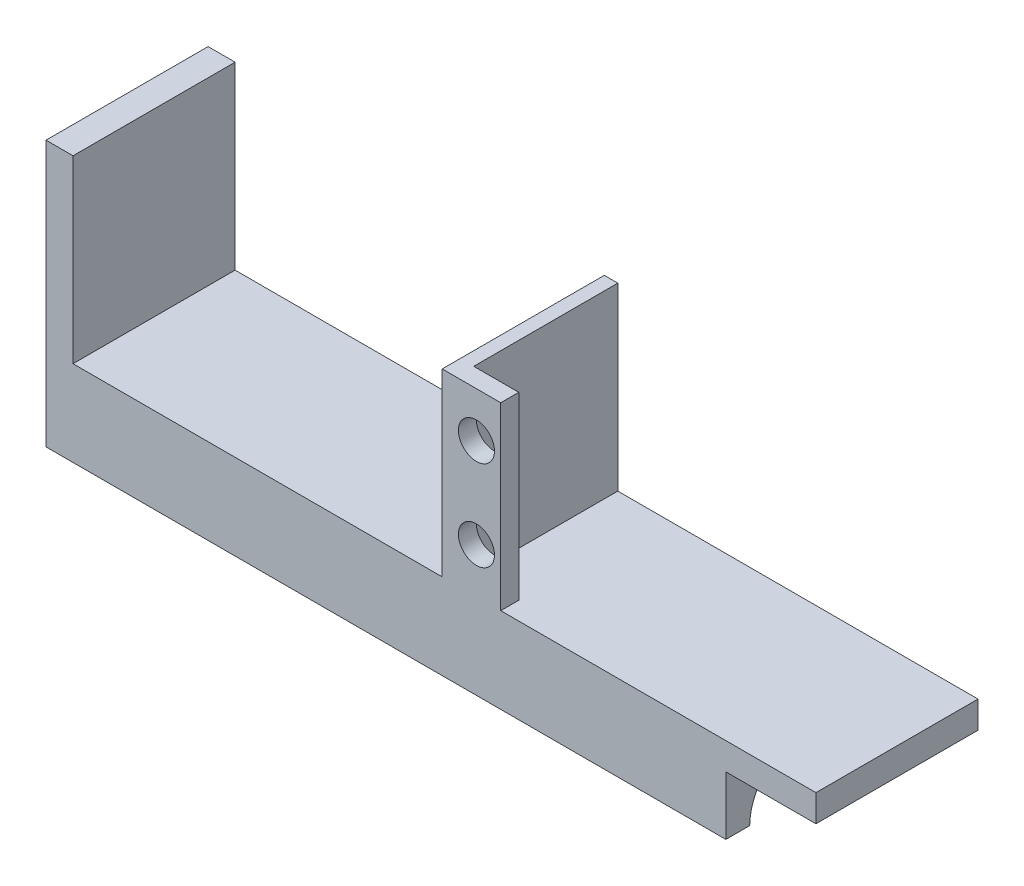
SolidWorks part; units mm, degrees
ref_plane "Front Plane" through (0, 0, 0) normal (0, 0, 1) x (1, 0, 0)
ref_plane "Top Plane" through (0, 0, 0) normal (0, 1, 0) x (1, 0, 0)
ref_plane "Right Plane" through (0, 0, 0) normal (1, 0, 0) x (0, 0, -1)
sketch "Sketch1" plane through (0, 0, 0) normal (0, 1, 0) x (1, 0, 0)
  line L1 (-22.75, -9) -> (22.75, -9)
  line L2 (-22.75, -9) -> (-22.75, 9)
  line L3 (-22.75, 9) -> (22.75, 9)
  line L4 (22.75, -9) -> (22.75, 9)
  line L5 (-22.75, -9) -> (22.75, 9) construction
  line L6 (-22.75, 9) -> (22.75, -9) construction
  point P0 (0, 0)
  dimension "D1" = 45.5
  dimension "D2" = 18
extrude "Boss-Extrude1" add sketch "Sketch1" along normal blind 3 contours L2 L3 L4 L1
sketch "Sketch2" plane through (0, 3, 0) normal (0, 1, 0) x (1, 0, 0)
  line L0 (-22.75, -9) -> (22.75, -9) construction
  line L1 (-22.75, 9) -> (-19.75, 9)
  line L2 (-22.75, 9) -> (-22.75, -9)
  line L3 (-22.75, -9) -> (-19.75, -9)
  line L4 (-19.75, 9) -> (-19.75, -9)
  line L16 (22.75, 9) -> (21.25, 9)
  line L17 (22.75, 9) -> (22.75, -9)
  line L18 (22.75, -9) -> (21.25, -9)
  line L19 (21.25, 9) -> (21.25, -9)
  dimension "D1" = 3
  dimension "D2" = 1.5
extrude "Boss-Extrude2" add sketch "Sketch2" along normal blind 20
sketch "Sketch6" plane through (22.75, 0, 0) normal (1, 0, 0) x (0, 0, -1)
  line L1 (-9, 23) -> (-7, 23)
  line L2 (-9, 23) -> (-9, 3)
  line L3 (-9, 3) -> (-7, 3)
  line L4 (-7, 23) -> (-7, 3)
  dimension "D1" = 20
  dimension "D2" = 2
extrude "Boss-Extrude5" add sketch "Sketch6" along normal blind 5
sketch "Sketch7" plane through (0, 0, 9) normal (0, 0, 1) x (1, 0, 0)
  line L0 (27.75, 23) -> (27.75, 3) construction
  line L1 (27.75, 3) -> (22.75, 3) construction
  line L2 (21.25, 23) -> (27.75, 23) construction
  circle A0 centre (25.05, 8) radius 2
  circle A1 centre (25.05, 18) radius 2
  dimension "D1" = 4
  dimension "D4" = 4
  dimension "D2" = 2.7
  dimension "D3" = 5
  dimension "D5" = 5
extrude "Cut-Extrude2" cut sketch "Sketch7" against normal blind 2
sketch3d "3DSketch1"
  line L1 (-22.75, 0, -9) -> (22.75, 0, -9) construction
  line L2 (-22.75, 0, 9) -> (-22.75, -6.5, 9)
  line L3 (-22.75, 0, 9) -> (-22.75, 0, -9)
  line L4 (-22.75, 0, -9) -> (-22.75, -6.5, -9)
  line L6 (-22.75, -6.5, -5.6458) -> (-22.75, -6.5, -9)
  line L7 (-22.75, -6.5, 6.3542) -> (-22.75, -6.5, 9)
  arc A0 (-22.75, -6.5, -5.6458) -> (-22.75, -6.5, 6.3542) centre (-22.75, -6.5, 0.3542) ccw
  point P2 (-16.75, -6.5, 0.3542)
  dimension "D1" = 12
  dimension "D2" = 6.5
  dimension "D5" = 0
extrude "Boss-Extrude9" add sketch "3DSketch1" along direction (1, 0, 0) on the side against the normal blind 75.5 contours L2 L7 A0 L6 L4 L3
sketch "Sketch9" plane through (22.75, 0, 0) normal (1, 0, 0) x (0, 0, -1)
  line L1 (-9, 0) -> (9, 0)
  line L2 (-9, 0) -> (-9, 3)
  line L3 (-9, 3) -> (9, 3)
  line L4 (9, 0) -> (9, 3)
extrude "Boss-Extrude10" add sketch "Sketch9" along normal blind 40
sketch3d "3DSketch2" plane through (0, 0, 0) normal (0, 0, 1) x (1, 0, 0)
  dimension "D1" = 30
